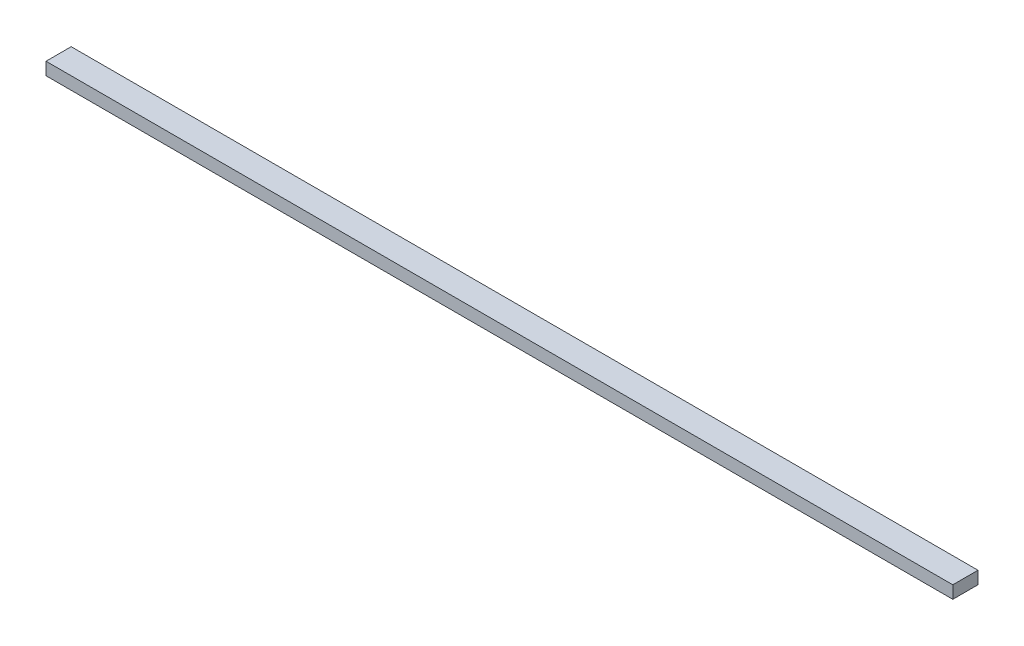
SolidWorks part; units mm, degrees
ref_plane "前视基准面" through (0, 0, 0) normal (0, 0, 1) x (1, 0, 0)
ref_plane "上视基准面" through (0, 0, 0) normal (0, 1, 0) x (1, 0, 0)
ref_plane "右视基准面" through (0, 0, 0) normal (1, 0, 0) x (0, 0, -1)
sketch "草图1" plane through (0, 0, 0) normal (0, 1, 0) x (1, 0, 0)
  line L0 (0, 0) -> (359.9, 0)
  line L1 (359.9, 0) -> (359.9, -10)
  line L2 (359.9, -10) -> (0, -10)
  line L3 (0, -10) -> (0, 0)
extrude "凸台-拉伸1" add sketch "草图1" along normal blind 5
